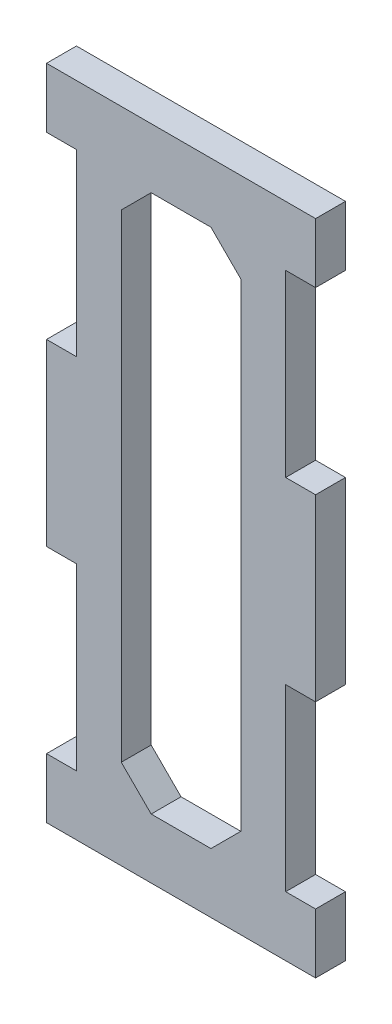
SolidWorks part; units mm, degrees
ref_plane "Plan de face" through (0, 0, 0) normal (0, 0, 1) x (1, 0, 0)
ref_plane "Plan de dessus" through (0, 0, 0) normal (0, 1, 0) x (1, 0, 0)
ref_plane "Plan de droite" through (0, 0, 0) normal (1, 0, 0) x (0, 0, -1)
sketch "Esquisse1" plane through (0, 0, 0) normal (0, 0, 1) x (1, 0, 0)
  line L0 (45, 220) -> (45, 0) construction
  line L1 (0, 0) -> (90, 0)
  line L2 (0, 0) -> (0, 220) construction
  line L3 (0, 220) -> (90, 220)
  line L4 (90, 0) -> (90, 220) construction
  line L5 (0, 0) -> (0, 20)
  line L6 (0, 20) -> (10, 20)
  line L7 (10, 20) -> (10, 80)
  line L8 (10, 80) -> (0, 80)
  line L9 (0, 80) -> (0, 140)
  line L10 (0, 140) -> (10, 140)
  line L11 (10, 140) -> (10, 200)
  line L12 (10, 200) -> (0, 200)
  line L13 (0, 200) -> (0, 220)
  line L14 (10, 200) -> (10, 220) construction
  line L15 (10, 140) -> (10, 80) construction
  line L16 (10, 20) -> (10, 0) construction
  line L17 (90, 0) -> (90, 20)
  line L18 (90, 20) -> (80, 20)
  line L19 (80, 20) -> (80, 80)
  line L20 (80, 80) -> (90, 80)
  line L21 (90, 80) -> (90, 140)
  line L22 (90, 140) -> (80, 140)
  line L23 (80, 140) -> (80, 200)
  line L24 (80, 200) -> (90, 200)
  line L25 (90, 200) -> (90, 220)
  dimension "D1" = 60
  dimension "D2" = 60
  dimension "D3" = 20
  dimension "D4" = 20
  dimension "D5" = 60
  dimension "D6" = 10
  dimension "D7" = 45
extrude "Boss.-Extru.1" add sketch "Esquisse1" along normal blind 10
sketch "Esquisse2" plane through (0, 0, 10) normal (0, 0, 1) x (1, 0, 0)
  line L0 (45, 220) -> (45, 0) construction
  line L1 (90, 220) -> (0, 220) construction
  line L2 (0, 0) -> (90, 0) construction
  line L3 (80, 20) -> (80, 80) construction
  line L4 (35, 200) -> (55, 200)
  line L5 (25, 190) -> (25, 30)
  line L6 (35, 20) -> (55, 20)
  line L7 (65, 190) -> (65, 30)
  line L8 (25, 190) -> (35, 200)
  line L9 (55, 200) -> (65, 190)
  line L10 (55, 20) -> (65, 30)
  line L11 (25, 30) -> (35, 20)
  line L12 (10, 80) -> (10, 20) construction
  point P6 (25, 200)
  point P7 (65, 20)
  point P8 (25, 20)
  point P9 (65, 200)
  dimension "D1" = 20
  dimension "D2" = 20
  dimension "D3" = 15
  dimension "D4" = 15
extrude "Enlèv. mat.-Extru.1" cut sketch "Esquisse2" against normal blind 10
